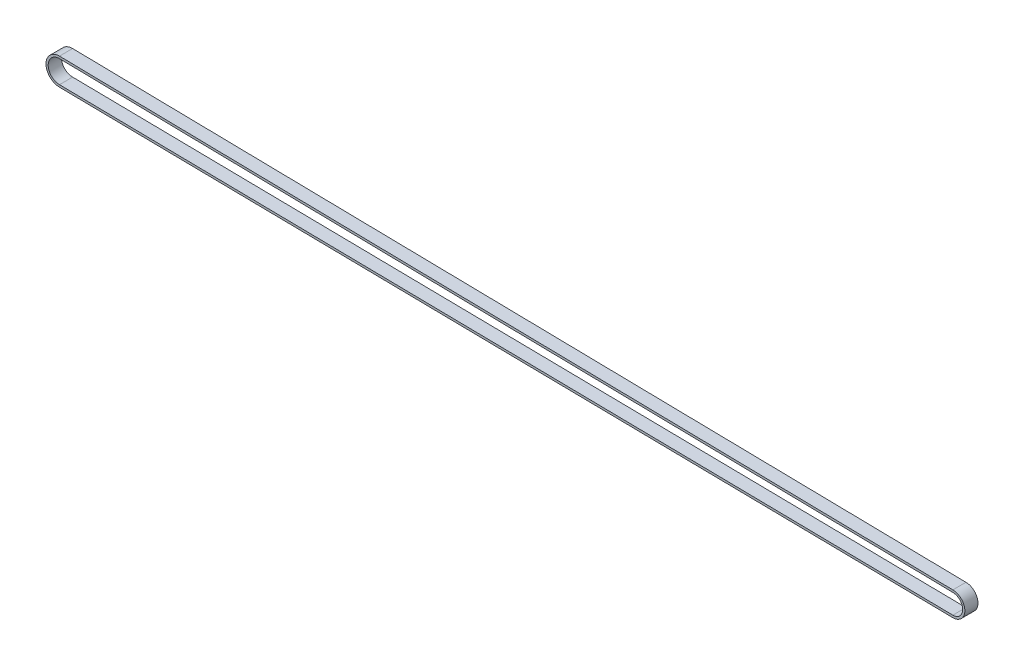
SolidWorks part; units mm, degrees
ref_plane "Front Plane" through (0, 0, 0) normal (0, 0, 1) x (1, 0, 0)
ref_plane "Top Plane" through (0, 0, 0) normal (0, 1, 0) x (1, 0, 0)
ref_plane "Right Plane" through (0, 0, 0) normal (1, 0, 0) x (0, 0, -1)
sketch "Sketch1" plane through (0, 0, 0) normal (0, 0, 1) x (1, 0, 0)
  line L0 (0, 5.15) -> (407.9379, -1.9706)
  line L1 (0, 5.15) -> (0, -5.15) construction
  line L2 (407.9379, -1.9706) -> (407.9379, -10.9706) construction
  line L3 (407.9379, -10.9706) -> (0, -5.15)
  line L4 (407.9379, -0.9706) -> (0, 6.15)
  line L5 (0, -6.15) -> (407.9379, -11.9706)
  arc A0 (0.1797, 5.1469) -> (0, -5.15) centre (0, 0) ccw
  arc A1 (407.9379, -10.9706) -> (407.9379, -1.9706) centre (407.9379, -6.4706) ccw
  arc A2 (0.2146, 6.1463) -> (0, -6.15) centre (0, 0) ccw
  arc A3 (407.7809, -11.9683) -> (407.9379, -0.9706) centre (407.9379, -6.4706) ccw
  dimension "D1" = 10.3
  dimension "D5" = 12.3
  dimension "D6" = 11
  dimension "D2" = 408
  dimension "D3" = 89
  dimension "D4" = 9
extrude "Boss-Extrude1" add sketch "Sketch1" along normal blind 6 contours L5 A3 L4 A2 A1 L3 A0 L0
